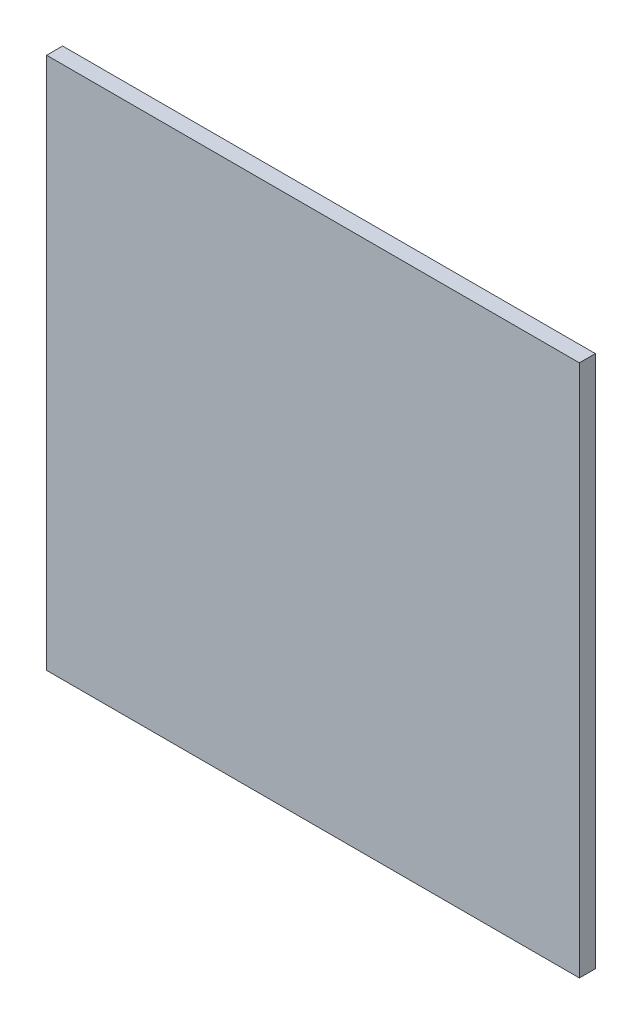
SolidWorks part; units mm, degrees
material "3.0205 (EN-AW 1200)"
ref_plane "Piano frontale" through (0, 0, 0) normal (0, 0, 1) x (1, 0, 0)
ref_plane "Piano superiore" through (0, 0, 0) normal (0, 1, 0) x (1, 0, 0)
ref_plane "Piano destro" through (0, 0, 0) normal (1, 0, 0) x (0, 0, -1)
sketch "Schizzo1" plane through (0, 0, 0) normal (0, 0, 1) x (1, 0, 0)
  line L1 (-250, -250) -> (250, -250)
  line L2 (-250, -250) -> (-250, 250)
  line L3 (-250, 250) -> (250, 250)
  line L4 (250, -250) -> (250, 250)
  line L5 (-250, -250) -> (250, 250) construction
  line L6 (-250, 250) -> (250, -250) construction
  point P0 (0, 0)
  dimension "D1" = 500
extrude "Estrusione-Estrusione1" add sketch "Schizzo1" along normal blind 15
